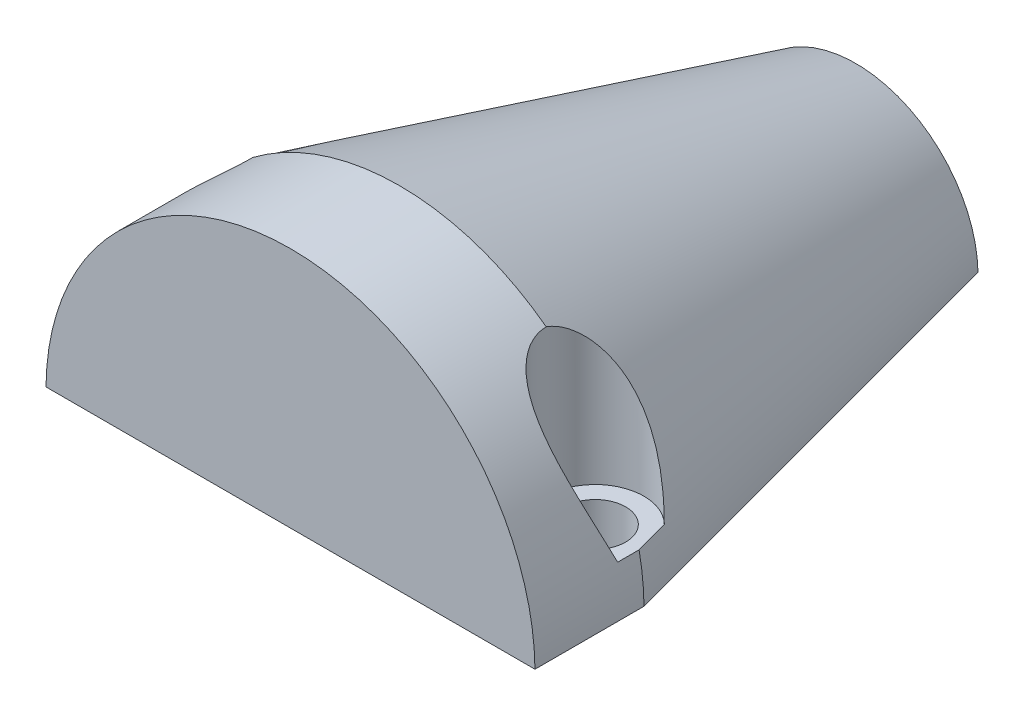
SolidWorks part; units mm, degrees
ref_plane "Front Plane" through (0, 0, 0) normal (0, 0, 1) x (1, 0, 0)
ref_plane "Top Plane" through (0, 0, 0) normal (0, 1, 0) x (1, 0, 0)
ref_plane "Right Plane" through (0, 0, 0) normal (1, 0, 0) x (0, 0, -1)
sketch "Sketch1" plane through (0, 0, 0) normal (0, 0, 1) x (1, 0, 0)
  circle A0 centre (0, 0) radius 12.7
extrude "Boss-Extrude1" add sketch "Sketch1" against normal blind 58.7248
ref_plane "Plane2" through (0, 0, -29.3624) normal (0, 0, -1) x (-1, 0, 0)
chamfer "Chamfer3" distance 6.35 angle 75 1 edges at (12.7, 0, -58.7248)
chamfer "Chamfer4" distance 6.35 angle 75 1 edges at (12.7, 0, 0)
sketch "Sketch2" plane through (0, 0, 0) normal (0, 1, 0) x (1, 0, 0)
  line L0 (-6.35, 0) -> (-12.7, 23.6985)
  line L1 (-12.7, 23.6985) -> (-12.7, 35.0263)
  line L2 (-12.7, 35.0263) -> (-6.35, 58.7248)
  line L3 (-6.35, 58.7248) -> (6.35, 58.7248)
  line L4 (6.35, 58.7248) -> (12.7, 35.0263)
  line L5 (12.7, 35.0263) -> (12.7, 23.6985)
  line L6 (12.7, 23.6985) -> (6.35, 0)
  line L7 (6.35, 0) -> (-6.35, 0)
extrude "Cut-Extrude1" cut sketch "Sketch2" against normal blind 58.7248
sketch "Sketch3" plane through (0, 0, 0) normal (0, 0, 1) x (1, 0, 0)
  line L0 (-12.7, 0) -> (12.7, 0)
  line L1 (0, 0) -> (0, 0.127) construction
  line L2 (0, 0.127) -> (12.6994, 0.127)
  line L3 (0, 0.127) -> (-12.6994, 0.127)
  arc A0 (12.7, 0) -> (12.6994, 0.127) centre (0, 0) ccw
  arc A1 (-12.6994, 0.127) -> (-12.7, 0) centre (0, 0) ccw
extrude "Cut-Extrude2" cut sketch "Sketch3" against normal blind 58.7248
sketch "Sketch4" plane through (0, 0, -29.3624) normal (0, 0, -1) x (-1, 0, 0)
  line L0 (0, 0.127) -> (-12.6994, 0.127)
  line L1 (-6.3487, 0.127) -> (6.3487, 0.127) construction
  line L2 (0, 0.127) -> (12.6994, 0.127)
  arc A0 (12.6994, 0.127) -> (-12.6994, 0.127) centre (0, 0.127) ccw
extrude "Cut-Extrude3" cut sketch "Sketch4" against normal through all
ref_plane "Plane3" through (0, 12.7, 0) normal (0, -1, 0) x (-1, 0, 0)
sketch "Sketch5" plane through (0, 12.7, 0) normal (0, -1, 0) x (-1, 0, 0)
  line L0 (-12.6994, 35.0263) -> (12.6994, 35.0263) construction
  line L3 (0, 35.0263) -> (0, 58.7248) construction
  line L4 (-6.3487, 58.7248) -> (6.3487, 58.7248) construction
  line L5 (0, 35.0263) -> (-10.16, 35.0263) construction
  circle A0 centre (-10.16, 35.0263) radius 1.5875
  circle A1 centre (10.16, 35.0263) radius 1.5875
extrude "Cut-Extrude4" cut sketch "Sketch5" along normal through all
sketch "Sketch6" plane through (0, 12.7, 0) normal (0, -1, 0) x (-1, 0, 0)
  line L0 (0, 58.7248) -> (0, 29.3624) construction
  line L1 (-6.3487, 58.7248) -> (6.3487, 58.7248) construction
  line L2 (3.4226, 29.3624) -> (-3.4226, 29.3624) construction
  circle A0 centre (-10.16, 35.0263) radius 2.54
  circle A1 centre (10.16, 35.0263) radius 2.54
extrude "Cut-Extrude5" cut sketch "Sketch6" along normal blind 10.16
